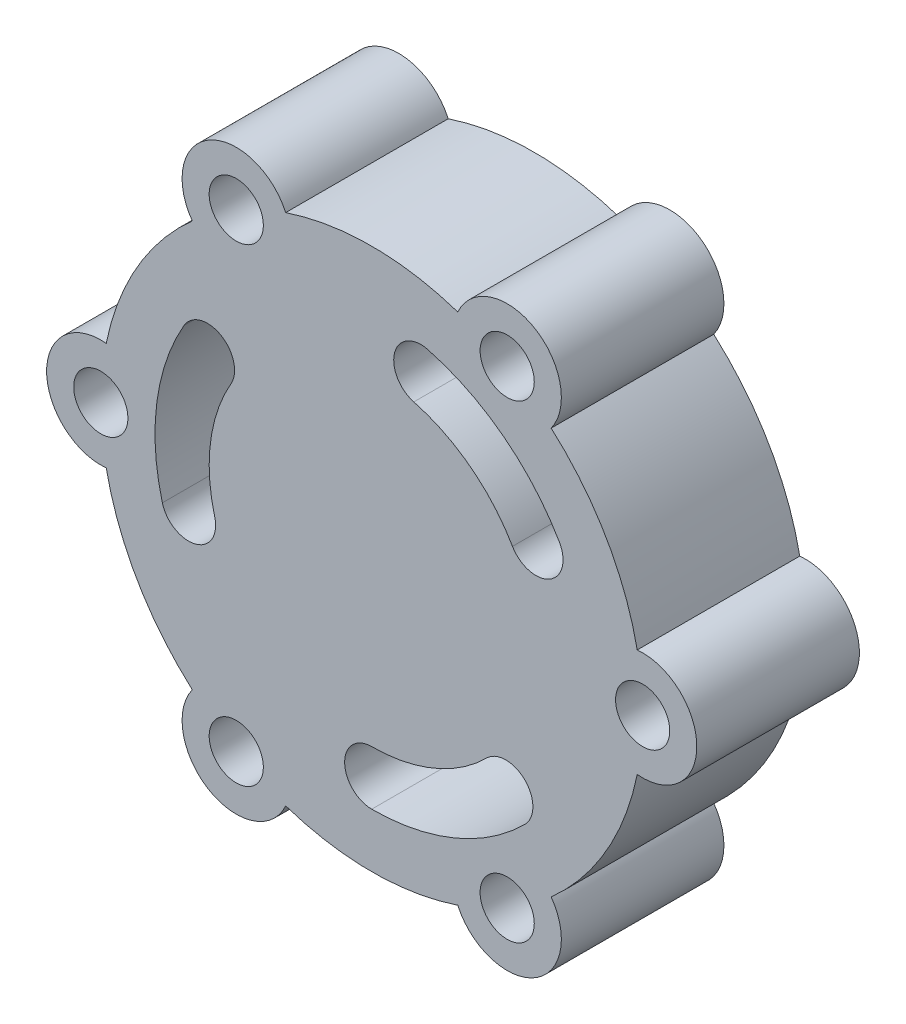
SolidWorks part; units mm, degrees
ref_plane "Front Plane" through (0, 0, 0) normal (0, 0, 1) x (1, 0, 0)
ref_plane "Top Plane" through (0, 0, 0) normal (0, 1, 0) x (1, 0, 0)
ref_plane "Right Plane" through (0, 0, 0) normal (1, 0, 0) x (0, 0, -1)
sketch "Sketch1" plane through (0, 0, 0) normal (0, 0, 1) x (1, 0, 0)
  line L0 (0, 0) -> (0, -13054.1451) construction
  line L1 (0, 0) -> (-13054.1451, 0) construction
  arc A19 (21, 60.0501) -> (36.8832, 32.5397) centre (70, 70) ccw
  circle A20 centre (70, 70) radius 35 construction
  arc A21 (21, 79.9499) -> (21, 60.0501) centre (20, 70) ccw
  circle A22 centre (20, 70) radius 5
  circle A23 centre (45, 26.6987) radius 5
  arc A24 (36.8832, 32.5397) -> (54.1168, 22.5898) centre (45, 26.6987) ccw
  circle A25 centre (95, 26.6987) radius 5
  arc A26 (85.8832, 22.5898) -> (103.1168, 32.5397) centre (95, 26.6987) ccw
  circle A27 centre (120, 70) radius 5
  arc A28 (119, 60.0501) -> (119, 79.9499) centre (120, 70) ccw
  circle A29 centre (95, 113.3013) radius 5
  arc A30 (103.1168, 107.4603) -> (85.8832, 117.4102) centre (95, 113.3013) ccw
  circle A31 centre (45, 113.3013) radius 5
  arc A32 (54.1168, 117.4102) -> (36.8832, 107.4603) centre (45, 113.3013) ccw
  arc A33 (36.8832, 107.4603) -> (21, 79.9499) centre (70, 70) ccw
  arc A34 (85.8832, 117.4102) -> (54.1168, 117.4102) centre (70, 70) ccw
  arc A35 (119, 79.9499) -> (103.1168, 107.4603) centre (70, 70) ccw
  arc A36 (103.1168, 32.5397) -> (119, 60.0501) centre (70, 70) ccw
  arc A37 (54.1168, 22.5898) -> (85.8832, 22.5898) centre (70, 70) ccw
  arc A38 (79.0587, 103.8074) -> (100.3109, 87.5) centre (70, 70) cw construction
  arc A39 (104.641, 90) -> (80.3528, 108.637) centre (70, 70) ccw
  arc A40 (95.9808, 85) -> (77.7646, 98.9778) centre (70, 70) ccw
  arc A41 (95.9808, 85) -> (104.641, 90) centre (100.3109, 87.5) ccw
  arc A42 (80.3528, 108.637) -> (77.7646, 98.9778) centre (79.0587, 103.8074) ccw
  arc A43 (94.7487, 45.2513) -> (70, 35) centre (70, 70) cw construction
  arc A44 (70, 30) -> (98.2843, 41.7157) centre (70, 70) ccw
  arc A45 (70, 40) -> (91.2132, 48.7868) centre (70, 70) ccw
  arc A46 (70, 40) -> (70, 30) centre (70, 35) ccw
  arc A47 (98.2843, 41.7157) -> (91.2132, 48.7868) centre (94.7487, 45.2513) ccw
  arc A48 (36.1926, 60.9413) -> (39.6891, 87.5) centre (70, 70) cw construction
  arc A49 (35.359, 90) -> (31.363, 59.6472) centre (70, 70) ccw
  arc A50 (44.0192, 85) -> (41.0222, 62.2354) centre (70, 70) ccw
  arc A51 (44.0192, 85) -> (35.359, 90) centre (39.6891, 87.5) ccw
  arc A52 (31.363, 59.6472) -> (41.0222, 62.2354) centre (36.1926, 60.9413) ccw
  point P34 (70, 70)
  point P35 (91.3067, 97.7674)
  point P44 (83.3939, 37.6642)
  point P51 (35.2994, 74.5684)
  point P56 (70, 70)
  dimension "D1" = 70
  dimension "D2" = 100
  dimension "D3" = 70
  dimension "D4" = 70
  dimension "D5" = 10
  dimension "D6" = 10
  dimension "D7" = 45
  dimension "D8" = 10
  dimension "D10" = 3
  dimension "D9" = 30
extrude "Boss-Extrude1" add sketch "Sketch1" along normal blind 30
